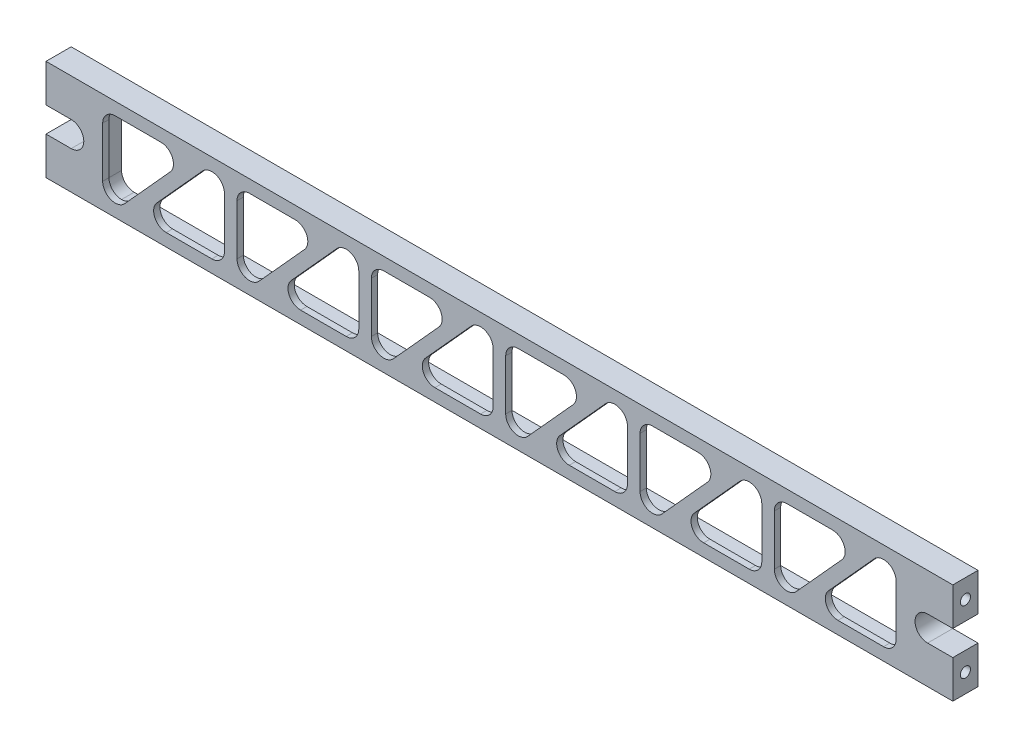
SolidWorks part; units mm, degrees
material "6061 Alloy"
ref_plane "Front Plane" through (0, 0, 0) normal (0, 0, 1) x (1, 0, 0)
ref_plane "Top Plane" through (0, 0, 0) normal (0, 1, 0) x (1, 0, 0)
ref_plane "Right Plane" through (0, 0, 0) normal (1, 0, 0) x (0, 0, -1)
sketch "Sketch1" plane through (0, 0, 0) normal (1, 0, 0) x (0, 0, -1)
  line L1 (0, 0) -> (12.7, 0)
  line L2 (0, 0) -> (0, 50.8)
  line L3 (0, 50.8) -> (12.7, 50.8)
  line L4 (12.7, 0) -> (12.7, 50.8)
  dimension "D1" = 12.7
  dimension "D2" = 50.8
extrude "Boss-Extrude1" add sketch "Sketch1" along normal mid plane 457.2
hole_wizard "1/4-20 Tapped Hole1" positions "3DSketch1" profile "Sketch2" tap size "1/4-20" standard "ANSI Inch"
sketch3d "3DSketch1"
  line L2 (228.6, 9.525, -6.35) -> (228.6, 41.275, -6.35) construction
  line L4 (228.6, 41.275, -6.35) -> (228.6, 50.8, -6.35) construction
  line L5 (228.6, 50.8, -12.7) -> (228.6, 50.8, 0) construction
  line L8 (228.6, 9.525, -6.35) -> (228.6, 0, -6.35) construction
  line L9 (228.6, 0, 0) -> (228.6, 0, -12.7) construction
  point P0 (228.6, 41.275, -6.35)
  point P2 (228.6, 9.525, -6.35)
  point P4 (-228.6, 9.525, -6.35)
  point P6 (-228.6, 41.275, -6.35)
  dimension "D1" = 31.75
sketch "Sketch2" plane through (228.6, 41.275, -6.35) normal (0, 1, 0) x (0, 0, -1)
  line L0 (0, 0) -> (0, 20.5838)
  line L1 (0, 20.5838) -> (2.5527, 19.05)
  line L2 (2.5527, 19.05) -> (2.5527, 0)
  line L5 (2.5527, 0) -> (0, 0)
  line L10 (0, 20.5838) -> (-2.5527, 19.05) construction
  line L11 (0, -6.35) -> (0, 107.95) construction
  dimension "Tap Drill Dia." = 5.1054
  dimension "Tap Drill Depth" = 19.05
  dimension "Drill Angle" = 118
sketch "Sketch4" plane through (0, 0, -12.7) normal (0, 0, -1) x (-1, 0, 0)
  line L0 (0, 0) -> (0, 3.175) construction
  line L1 (196.85, 47.625) -> (-196.85, 47.625)
  line L2 (203.2, 41.275) -> (203.2, 9.525)
  line L3 (196.85, 3.175) -> (-196.85, 3.175)
  line L4 (-203.2, 41.275) -> (-203.2, 9.525)
  line L5 (-228.6, 0) -> (228.6, 0) construction
  line L6 (0, 47.625) -> (0, 50.8) construction
  line L7 (-228.6, 50.8) -> (228.6, 50.8) construction
  line L8 (228.6, 25.4) -> (203.2, 25.4) construction
  line L9 (228.6, 0) -> (228.6, 50.8) construction
  line L10 (-228.6, 25.4) -> (-203.2, 25.4) construction
  line L11 (-228.6, 0) -> (-228.6, 50.8) construction
  arc A0 (-196.85, 3.175) -> (-203.2, 9.525) centre (-196.85, 9.525) cw
  arc A1 (-196.85, 47.625) -> (-203.2, 41.275) centre (-196.85, 41.275) ccw
  arc A2 (203.2, 9.525) -> (196.85, 3.175) centre (196.85, 9.525) cw
  arc A3 (196.85, 47.625) -> (203.2, 41.275) centre (196.85, 41.275) cw
  dimension "D1" = 6.35
  dimension "D2" = 3.175
  dimension "D3" = 25.4
extrude "Cut-Extrude1" cut sketch "Sketch4" against normal blind 9.525
sketch "Sketch5" plane through (0, 0, -3.175) normal (0, 0, -1) x (-1, 0, 0)
  line L0 (-200.025, 38.1) -> (-200.025, 12.7)
  line L1 (-193.675, 6.35) -> (-170.6858, 6.35)
  line L2 (-165.9778, 16.9611) -> (-188.967, 42.3611)
  line L3 (-172.6889, 33.8389) -> (-149.6997, 8.4389)
  line L4 (-138.6417, 12.7) -> (-138.6417, 38.1)
  line L5 (-144.9917, 44.45) -> (-167.9809, 44.45)
  line L6 (-132.2917, 38.1) -> (-132.2917, 12.7)
  line L7 (-156.4863, 44.45) -> (-156.4863, 47.625) construction
  line L8 (196.85, 47.625) -> (-196.85, 47.625) construction
  line L9 (-125.9417, 6.35) -> (-102.9524, 6.35)
  line L10 (-182.1804, 6.35) -> (-182.1804, 3.175) construction
  line L11 (-196.85, 3.175) -> (196.85, 3.175) construction
  line L12 (-98.2444, 16.9611) -> (-121.2337, 42.3611)
  line L13 (-200.025, 25.4) -> (-203.2, 25.4) construction
  line L14 (-203.2, 41.275) -> (-203.2, 9.525) construction
  line L15 (-177.4724, 29.6611) -> (-172.7644, 33.9223) construction
  line L16 (-104.9556, 33.8389) -> (-81.9663, 8.4389)
  line L17 (-70.9083, 12.7) -> (-70.9083, 38.1)
  line L18 (-77.2583, 44.45) -> (-100.2476, 44.45)
  line L19 (-109.7391, 29.6611) -> (-105.0311, 33.9223) construction
  line L20 (-64.5583, 38.1) -> (-64.5583, 12.7)
  line L21 (-58.2083, 6.35) -> (-35.2191, 6.35)
  line L22 (-30.5111, 16.9611) -> (-53.5003, 42.3611)
  line L23 (-37.2222, 33.8389) -> (-14.233, 8.4389)
  line L24 (-3.175, 12.7) -> (-3.175, 38.1)
  line L25 (-9.525, 44.45) -> (-32.5142, 44.45)
  line L26 (-42.0057, 29.6611) -> (-37.2977, 33.9223) construction
  line L27 (3.175, 38.1) -> (3.175, 12.7)
  line L28 (9.525, 6.35) -> (32.5142, 6.35)
  line L29 (37.2222, 16.9611) -> (14.233, 42.3611)
  line L30 (30.5111, 33.8389) -> (53.5003, 8.4389)
  line L31 (64.5583, 12.7) -> (64.5583, 38.1)
  line L32 (58.2083, 44.45) -> (35.2191, 44.45)
  line L33 (25.7276, 29.6611) -> (30.4356, 33.9223) construction
  line L34 (70.9083, 38.1) -> (70.9083, 12.7)
  line L35 (77.2583, 6.35) -> (100.2476, 6.35)
  line L36 (104.9556, 16.9611) -> (81.9663, 42.3611)
  line L37 (98.2444, 33.8389) -> (121.2337, 8.4389)
  line L38 (132.2917, 12.7) -> (132.2917, 38.1)
  line L39 (125.9417, 44.45) -> (102.9524, 44.45)
  line L40 (93.4609, 29.6611) -> (98.1689, 33.9223) construction
  line L41 (138.6417, 38.1) -> (138.6417, 12.7)
  line L42 (144.9917, 6.35) -> (167.9809, 6.35)
  line L43 (172.6889, 16.9611) -> (149.6997, 42.3611)
  line L44 (165.9778, 33.8389) -> (188.967, 8.4389)
  line L45 (200.025, 12.7) -> (200.025, 38.1)
  line L46 (193.675, 44.45) -> (170.6858, 44.45)
  line L47 (161.1943, 29.6611) -> (165.9023, 33.9223) construction
  line L48 (-138.6417, 25.4) -> (-132.2917, 25.4) construction
  line L49 (200.025, 25.4) -> (203.2, 25.4) construction
  line L50 (203.2, 9.525) -> (203.2, 41.275) construction
  arc A0 (-172.6889, 33.8389) -> (-167.9809, 44.45) centre (-167.9809, 38.1) cw
  arc A1 (-138.6417, 38.1) -> (-144.9917, 44.45) centre (-144.9917, 38.1) ccw
  arc A2 (-149.6997, 8.4389) -> (-138.6417, 12.7) centre (-144.9917, 12.7) ccw
  arc A3 (-170.6858, 6.35) -> (-165.9778, 16.9611) centre (-170.6858, 12.7) ccw
  arc A4 (-200.025, 12.7) -> (-193.675, 6.35) centre (-193.675, 12.7) ccw
  arc A5 (-200.025, 38.1) -> (-188.967, 42.3611) centre (-193.675, 38.1) cw
  arc A6 (-104.9556, 33.8389) -> (-100.2476, 44.45) centre (-100.2476, 38.1) cw
  arc A7 (-70.9083, 38.1) -> (-77.2583, 44.45) centre (-77.2583, 38.1) ccw
  arc A8 (-81.9663, 8.4389) -> (-70.9083, 12.7) centre (-77.2583, 12.7) ccw
  arc A9 (-102.9524, 6.35) -> (-98.2444, 16.9611) centre (-102.9524, 12.7) ccw
  arc A10 (-132.2917, 12.7) -> (-125.9417, 6.35) centre (-125.9417, 12.7) ccw
  arc A11 (-132.2917, 38.1) -> (-121.2337, 42.3611) centre (-125.9417, 38.1) cw
  arc A12 (-37.2222, 33.8389) -> (-32.5142, 44.45) centre (-32.5142, 38.1) cw
  arc A13 (-3.175, 38.1) -> (-9.525, 44.45) centre (-9.525, 38.1) ccw
  arc A14 (-14.233, 8.4389) -> (-3.175, 12.7) centre (-9.525, 12.7) ccw
  arc A15 (-35.2191, 6.35) -> (-30.5111, 16.9611) centre (-35.2191, 12.7) ccw
  arc A16 (-64.5583, 12.7) -> (-58.2083, 6.35) centre (-58.2083, 12.7) ccw
  arc A17 (-64.5583, 38.1) -> (-53.5003, 42.3611) centre (-58.2083, 38.1) cw
  arc A18 (30.5111, 33.8389) -> (35.2191, 44.45) centre (35.2191, 38.1) cw
  arc A19 (64.5583, 38.1) -> (58.2083, 44.45) centre (58.2083, 38.1) ccw
  arc A20 (53.5003, 8.4389) -> (64.5583, 12.7) centre (58.2083, 12.7) ccw
  arc A21 (32.5142, 6.35) -> (37.2222, 16.9611) centre (32.5142, 12.7) ccw
  arc A22 (3.175, 12.7) -> (9.525, 6.35) centre (9.525, 12.7) ccw
  arc A23 (3.175, 38.1) -> (14.233, 42.3611) centre (9.525, 38.1) cw
  arc A24 (98.2444, 33.8389) -> (102.9524, 44.45) centre (102.9524, 38.1) cw
  arc A25 (132.2917, 38.1) -> (125.9417, 44.45) centre (125.9417, 38.1) ccw
  arc A26 (121.2337, 8.4389) -> (132.2917, 12.7) centre (125.9417, 12.7) ccw
  arc A27 (100.2476, 6.35) -> (104.9556, 16.9611) centre (100.2476, 12.7) ccw
  arc A28 (70.9083, 12.7) -> (77.2583, 6.35) centre (77.2583, 12.7) ccw
  arc A29 (70.9083, 38.1) -> (81.9663, 42.3611) centre (77.2583, 38.1) cw
  arc A30 (165.9778, 33.8389) -> (170.6858, 44.45) centre (170.6858, 38.1) cw
  arc A31 (200.025, 38.1) -> (193.675, 44.45) centre (193.675, 38.1) ccw
  arc A32 (188.967, 8.4389) -> (200.025, 12.7) centre (193.675, 12.7) ccw
  arc A33 (167.9809, 6.35) -> (172.6889, 16.9611) centre (167.9809, 12.7) ccw
  arc A34 (138.6417, 12.7) -> (144.9917, 6.35) centre (144.9917, 12.7) ccw
  arc A35 (138.6417, 38.1) -> (149.6997, 42.3611) centre (144.9917, 38.1) cw
  dimension "D1" = 3.175
  dimension "D2" = 6.35
  dimension "D4" = 6
  dimension "D3" = 6.35
extrude "Cut-Extrude2" cut sketch "Sketch5" against normal through all
sketch "Sketch6" plane through (0, 0, 0) normal (0, 0, 1) x (1, 0, 0)
  line L0 (0, 0) -> (0, 50.8) construction
  line L1 (228.6, 50.8) -> (-228.6, 50.8) construction
  line L2 (-215.9, 31.75) -> (-228.6, 31.75)
  line L3 (-228.6, 50.8) -> (-228.6, 0) construction
  line L4 (-228.6, 31.75) -> (-228.6, 19.05)
  line L5 (-228.6, 19.05) -> (-215.9, 19.05)
  line L6 (228.6, 19.05) -> (215.9, 19.05)
  line L7 (-203.2, 9.525) -> (-203.2, 41.275) construction
  line L8 (228.6, 31.75) -> (228.6, 19.05)
  line L9 (215.9, 31.75) -> (228.6, 31.75)
  arc A0 (-215.9, 19.05) -> (-215.9, 31.75) centre (-215.9, 25.4) ccw
  arc A1 (215.9, 19.05) -> (215.9, 31.75) centre (215.9, 25.4) cw
  point P8 (-228.6, 25.4)
  point P18 (228.6, 25.4)
  point P19 (-209.55, 25.4)
  dimension "D1" = 12.7
  dimension "D2" = 6.35
extrude "Cut-Extrude3" cut sketch "Sketch6" against normal through all
